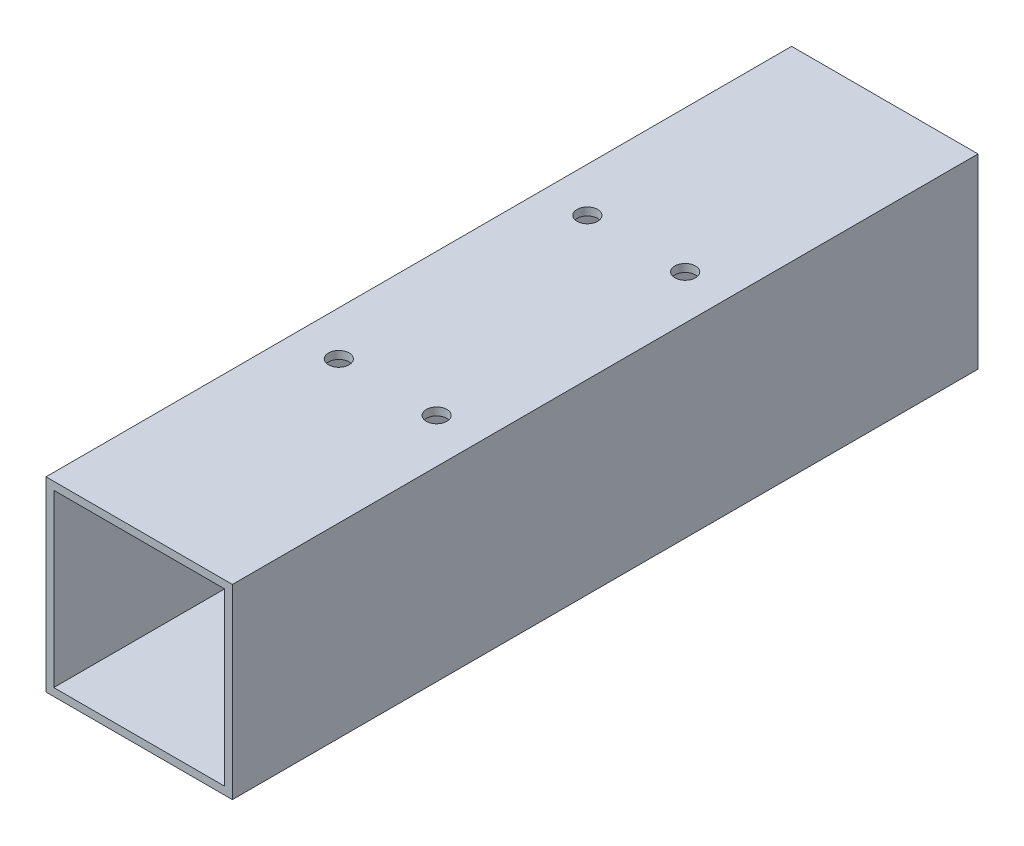
SolidWorks part; units mm, degrees
ref_plane "Front Plane" through (0, 0, 0) normal (0, 0, 1) x (1, 0, 0)
ref_plane "Top Plane" through (0, 0, 0) normal (0, 1, 0) x (1, 0, 0)
ref_plane "Right Plane" through (0, 0, 0) normal (1, 0, 0) x (0, 0, -1)
sketch "Sketch1" plane through (0, 0, 0) normal (0, 0, 1) x (1, 0, 0)
  line L0 (-34.925, 34.925) -> (34.925, 34.925)
  line L2 (-38.1, 38.1) -> (38.1, 38.1)
  line L3 (-38.1, 38.1) -> (-38.1, -38.1)
  line L4 (-38.1, -38.1) -> (38.1, -38.1)
  line L5 (38.1, 38.1) -> (38.1, -38.1)
  line L10 (34.925, 34.925) -> (34.925, -34.925)
  line L11 (-34.925, -34.925) -> (34.925, -34.925)
  line L12 (-34.925, 34.925) -> (-34.925, -34.925)
  point P12 (0, 38.1)
  point P14 (38.1, 0)
  dimension "Wall Thickness" = 3.175
  dimension "Outside Width" = 76.2
  dimension "Outside Height" = 76.2
  dimension "Inside Height" = 69.85
  dimension "Inside Width" = 69.85
sketch "Sketch2" plane through (0, 0, 0) normal (1, 0, 0) x (0, 0, -1)
  line L0 (152.4, 0) -> (-152.4, 0)
  point P4 (0, 0)
  point P7 (-152.4, 0)
  point P10 (152.4, 0)
  dimension "Length" = 304.8
sketch "Sketch3" plane through (0, 0, 0) normal (0, 0, 1) x (1, 0, 0)
  line L21 (38.1, 38.1) -> (-38.1, 38.1)
  line L22 (38.1, -38.1) -> (38.1, 38.1)
  line L23 (-38.1, -38.1) -> (38.1, -38.1)
  line L24 (-38.1, 38.1) -> (-38.1, -38.1)
  line L25 (38.1, 38.1) -> (-38.1, 38.1)
  line L26 (38.1, -38.1) -> (38.1, 38.1)
  line L27 (-38.1, -38.1) -> (38.1, -38.1)
  line L28 (-38.1, 38.1) -> (-38.1, -38.1)
  line L29 (34.925, 34.925) -> (-34.925, 34.925)
  line L30 (34.925, -34.925) -> (34.925, 34.925)
  line L31 (-34.925, -34.925) -> (34.925, -34.925)
  line L32 (-34.925, 34.925) -> (-34.925, -34.925)
  line L33 (34.925, 34.925) -> (-34.925, 34.925)
  line L34 (34.925, -34.925) -> (34.925, 34.925)
  line L35 (-34.925, -34.925) -> (34.925, -34.925)
  line L36 (-34.925, 34.925) -> (-34.925, -34.925)
  dimension "D1" = 0
  dimension "D2" = 0
extrude "Boss-Extrude1" add sketch "Sketch3" along normal up to vertex (152.4 mm away) and the other way up to vertex (152.4 mm away) up to point (0, 0, 152.4) other way up to point (0, 0, -152.4)
sketch "Drawing Reference" plane through (0, 0, 0) normal (1, 0, 0) x (0, 0, -1)
  line L0 (-152.4, 0) -> (152.4, 0) construction
  line L1 (0, -38.1) -> (0, 38.1) construction
  line L2 (-152.4, -38.1) -> (152.4, -38.1) construction
  line L5 (-152.4, 38.1) -> (152.4, 38.1) construction
  point P7 (-129.54, 0)
  point P8 (129.54, 0)
  dimension "D1" = 22.86
hole_wizard "5/16 Clearance Hole3" positions "Sketch12" profile "Sketch13" hole size "5/16" standard "ANSI Inch" end condition through all
sketch "Sketch12" plane through (0, -38.1, 0) normal (0, -1, 0) x (-1, 0, 0)
  line L1 (-20, -50.8) -> (20, -50.8)
  line L2 (-20, -50.8) -> (-20, 50.8)
  line L3 (-20, 50.8) -> (20, 50.8)
  line L4 (20, -50.8) -> (20, 50.8)
  line L5 (-20, -50.8) -> (20, 50.8) construction
  line L6 (-20, 50.8) -> (20, -50.8) construction
  point P2 (20, 50.8)
  point P127 (-20, -50.8)
  point P128 (-20, 50.8)
  point P129 (20, -50.8)
  point P143 (0, 0)
  point P145 (0, 0)
  point P146 (0, 0)
  point P147 (-20.998, 50.8)
  point P148 (0, 0)
  dimension "D1" = 101.6
  dimension "D2" = 40
sketch "Sketch13" plane through (-20, -38.1, -50.8) normal (1, 0, 0) x (0, 0, -1)
  line L0 (0, 0) -> (0, 76.2)
  line L1 (0, 76.2) -> (4.2164, 76.2)
  line L2 (4.2164, 76.2) -> (4.2164, 0)
  line L5 (4.2164, 0) -> (0, 0)
  line L11 (0, -6.35) -> (0, 107.95) construction
  dimension "Thru Hole Dia." = 8.4328
  dimension "Thru Hole Depth" = 76.2
hole_wizard "1/2 Clearance Hole1" positions "Sketch14" profile "Sketch15" hole size "1/2" standard "ANSI Inch"
sketch "Sketch14" plane through (0, -38.1, 0) normal (0, -1, 0) x (-1, 0, 0)
  point P0 (-20, 50.8)
  point P3 (20, 50.8)
  point P6 (-20, -50.8)
  point P9 (20, -50.8)
sketch "Sketch15" plane through (20, -38.1, -50.8) normal (1, 0, 0) x (0, 0, -1)
  line L0 (0, 0) -> (0, 7.2285)
  line L1 (0, 7.2285) -> (6.7462, 3.175)
  line L2 (6.7462, 3.175) -> (6.7462, 0)
  line L5 (6.7462, 0) -> (0, 0)
  line L10 (0, 7.2285) -> (-6.7462, 3.175) construction
  line L11 (0, -6.35) -> (0, 107.95) construction
  dimension "Hole Dia." = 13.4925
  dimension "Hole Depth" = 3.175
  dimension "Drill Angle" = 118
equation "\"D1@Drawing Reference\"=\"Outside Width@Sketch1\" * .3"
